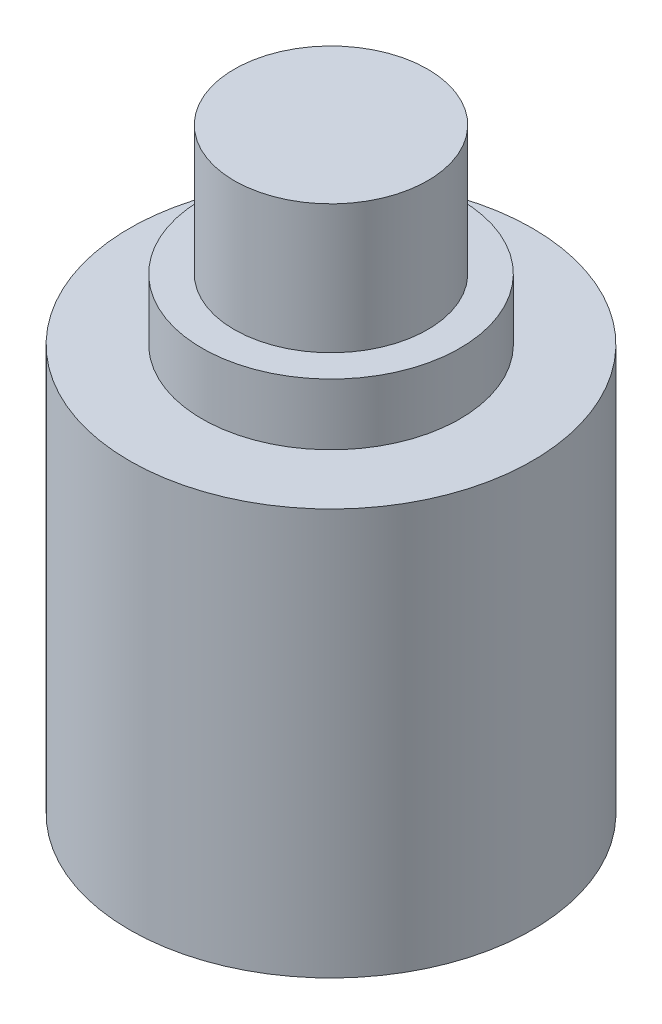
SolidWorks part; units mm, degrees
ref_plane "前视基准面" through (0, 0, 0) normal (0, 0, 1) x (1, 0, 0)
ref_plane "上视基准面" through (0, 0, 0) normal (0, 1, 0) x (1, 0, 0)
ref_plane "右视基准面" through (0, 0, 0) normal (1, 0, 0) x (0, 0, -1)
sketch "草图1" plane through (0, 0, 0) normal (0, 1, 0) x (1, 0, 0)
  circle A0 centre (0, 0) radius 12.5
  dimension "D1" = 25
extrude "凸台-拉伸1" add sketch "草图1" along normal blind 25.2
sketch "草图2" plane through (0, 25.2, 0) normal (0, 1, 0) x (1, 0, 0)
  circle A0 centre (0, 0) radius 8
  dimension "D1" = 16
extrude "凸台-拉伸2" add sketch "草图2" along normal blind 3.8
sketch "草图3" plane through (0, 29, 0) normal (0, 1, 0) x (1, 0, 0)
  circle A0 centre (0, 0) radius 6
  dimension "D1" = 12
extrude "凸台-拉伸3" add sketch "草图3" along normal blind 8
